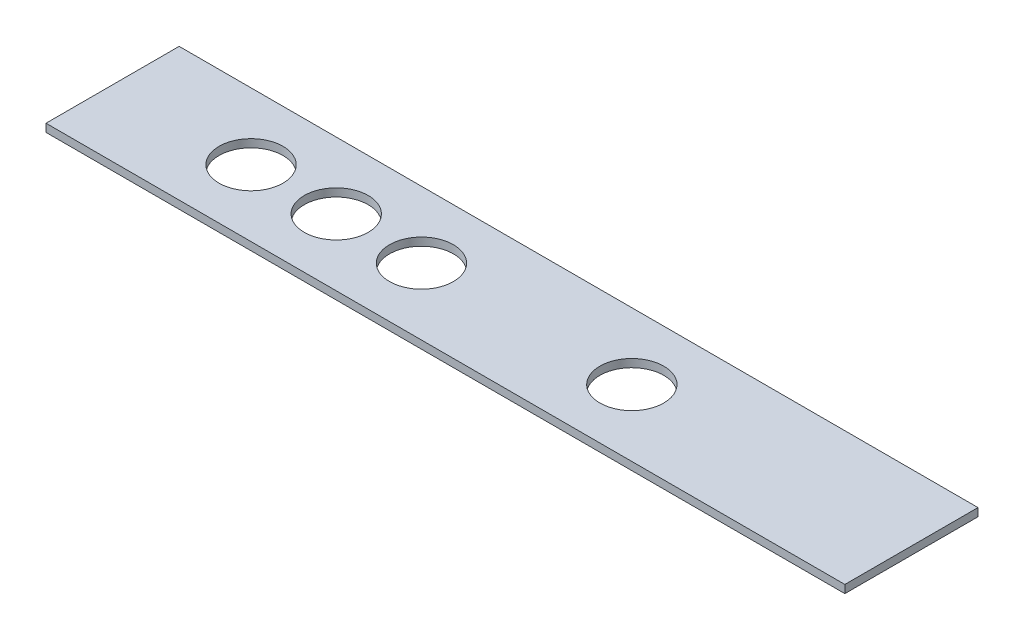
SolidWorks part; units mm, degrees
ref_plane "Front Plane" through (0, 0, 0) normal (0, 0, 1) x (1, 0, 0)
ref_plane "Top Plane" through (0, 0, 0) normal (0, 1, 0) x (1, 0, 0)
ref_plane "Right Plane" through (0, 0, 0) normal (1, 0, 0) x (0, 0, -1)
sketch "Sketch1" plane through (0, 0, 0) normal (0, 1, 0) x (1, 0, 0)
  line L0 (-148.6381, 28.1128) -> (-96.6381, 28.1128) construction
  line L1 (-148.6381, 53.1128) -> (151.3619, 53.1128)
  line L2 (-148.6381, 53.1128) -> (-148.6381, 3.1128)
  line L3 (-148.6381, 3.1128) -> (151.3619, 3.1128)
  line L4 (151.3619, 53.1128) -> (151.3619, 3.1128)
  line L5 (-96.6381, 28.1128) -> (-64.6381, 28.1128) construction
  line L6 (-64.6381, 28.1128) -> (-32.6381, 28.1128) construction
  line L7 (151.3619, 28.1128) -> (46.3619, 28.1128) construction
  circle A0 centre (-96.6381, 28.1128) radius 12
  circle A1 centre (-64.6381, 28.1128) radius 12
  circle A2 centre (-32.6381, 28.1128) radius 12
  circle A3 centre (46.3619, 28.1128) radius 12
  dimension "D1" = 300
  dimension "D2" = 50
  dimension "D3" = 32
  dimension "D4" = 32
  dimension "D5" = 52
  dimension "D6" = 105
extrude "Boss-Extrude1" add sketch "Sketch1" along normal blind 3 contours L2 L1 L4 L3 | A2 | A3 | A1 | A0
